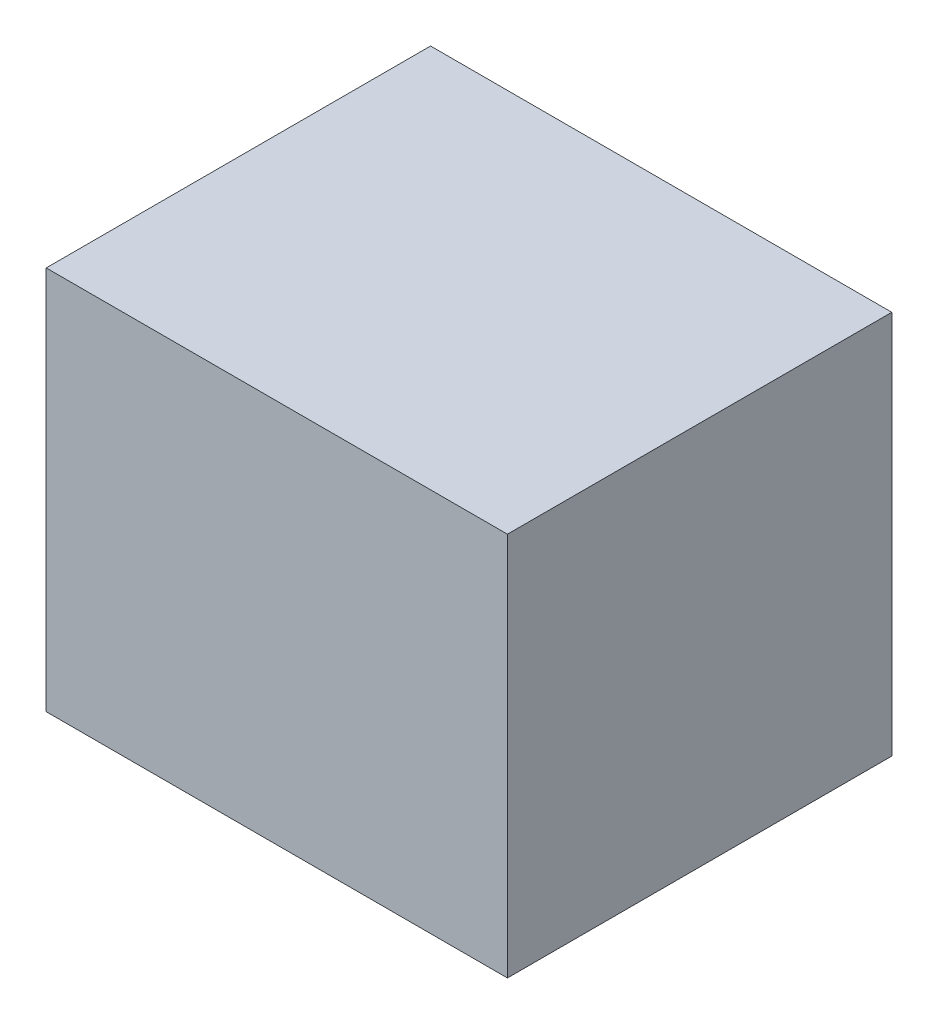
SolidWorks part; units mm, degrees
material "Gray Cast Iron"
ref_plane "Front Plane" through (0, 0, 0) normal (0, 0, 1) x (1, 0, 0)
ref_plane "Top Plane" through (0, 0, 0) normal (0, 1, 0) x (1, 0, 0)
ref_plane "Right Plane" through (0, 0, 0) normal (1, 0, 0) x (0, 0, -1)
sketch "Sketch1" plane through (0, 0, 0) normal (0, 0, 1) x (1, 0, 0)
  line L1 (0, 0) -> (600, 0)
  line L2 (0, 0) -> (0, 500)
  line L3 (0, 500) -> (600, 500)
  line L4 (600, 0) -> (600, 500)
  dimension "Length" = 600
  dimension "Width" = 500
extrude "Boss-Extrude1" add sketch "Sketch1" along normal blind 500
shell "Shell1" [suppressed] thickness 20
shell "Shell2" [suppressed] thickness 20
shell "Shell3" [suppressed] thickness 20
shell "Shell4" [suppressed] thickness 20
shell "Shell5" [suppressed] thickness 20
